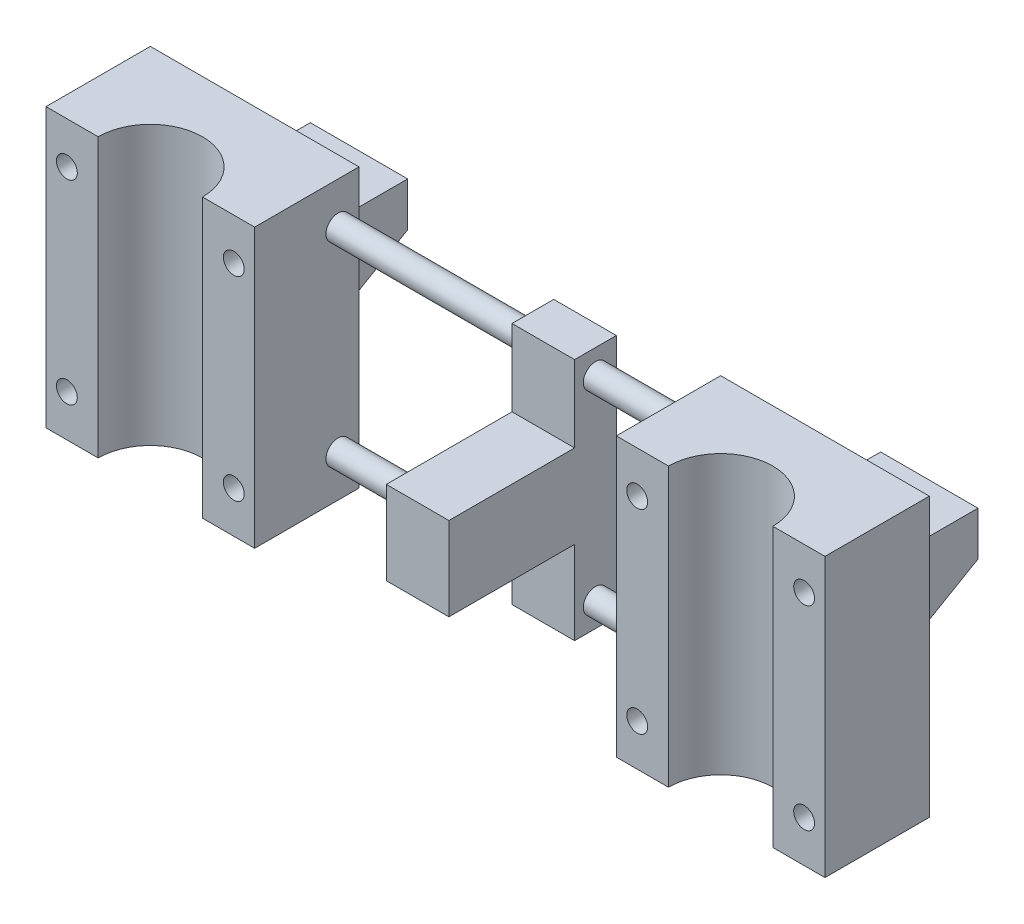
SolidWorks part; units mm, degrees
ref_plane "Front Plane" through (0, 0, 0) normal (0, 0, 1) x (1, 0, 0)
ref_plane "Top Plane" through (0, 0, 0) normal (0, 1, 0) x (1, 0, 0)
ref_plane "Right Plane" through (0, 0, 0) normal (1, 0, 0) x (0, 0, -1)
sketch "Sketch1" plane through (0, 0, 0) normal (0, 0, 1) x (1, 0, 0)
  line L1 (0, 0) -> (30, 0)
  line L2 (0, 0) -> (0, 40)
  line L3 (0, 40) -> (30, 40)
  line L4 (30, 0) -> (30, 40)
  dimension "D1" = 40
  dimension "D2" = 30
extrude "Boss-Extrude1" add sketch "Sketch1" along normal blind 15
sketch "Sketch2" plane through (0, 40, 0) normal (0, 1, 0) x (1, 0, 0)
  line L0 (30, -15) -> (0, -15) construction
  line L1 (7.5, -15) -> (22.5, -15)
  arc A0 (22.5, -15) -> (7.5, -15) centre (15, -15) ccw
  dimension "D1" = 15
extrude "Cut-Extrude1" cut sketch "Sketch2" against normal blind 49
sketch "Sketch3" plane through (0, 0, 15) normal (0, 0, 1) x (1, 0, 0)
  line L0 (7.5, 40) -> (0, 40) construction
  line L1 (0, 40) -> (0, 0) construction
  line L2 (30, 0) -> (30, 40) construction
  line L3 (30, 40) -> (22.5, 40) construction
  line L4 (22.5, 0) -> (30, 0) construction
  line L5 (0, 0) -> (7.5, 0) construction
  circle A0 centre (3, 34) radius 1.5
  circle A1 centre (3, 6) radius 1.5
  circle A2 centre (27, 34) radius 1.5
  circle A3 centre (27, 6) radius 1.5
  point P19 (26.25, 0)
  point P25 (3.75, 0)
  dimension "D1" = 3
  dimension "D2" = 3
  dimension "D3" = 3
  dimension "D4" = 3
  dimension "D5" = 6
  dimension "D6" = 3
  dimension "D7" = 3
  dimension "D8" = 6
  dimension "D9" = 6
  dimension "D10" = 3
  dimension "D11" = 3
  dimension "D12" = 6
extrude "Cut-Extrude2" cut sketch "Sketch3" against normal blind 49
sketch "Sketch4" plane through (30, 0, 0) normal (1, 0, 0) x (0, 0, -1)
  line L0 (-15, 40) -> (0, 40) construction
  line L1 (-15, 0) -> (0, 0) construction
  line L2 (0, 0) -> (0, 40) construction
  circle A0 centre (-3, 34) radius 1.75
  circle A1 centre (-3, 6) radius 1.75
  dimension "D1" = 3.5
  dimension "D2" = 3.5
  dimension "D3" = 6
  dimension "D4" = 6
  dimension "D5" = 3
  dimension "D6" = 3
extrude "Boss-Extrude2" add sketch "Sketch4" along normal blind 28
sketch "Sketch5" plane through (58, 0, 0) normal (1, 0, 0) x (0, 0, -1)
  line L0 (0, 0) -> (0, 40) construction
  line L1 (0, 37.5) -> (-6, 37.5)
  line L2 (0, 37.5) -> (0, 2.5)
  line L3 (0, 2.5) -> (-6, 2.5)
  line L4 (-6, 37.5) -> (-6, 2.5)
  circle A0 centre (-3, 34) radius 1.75 construction
  point P6 (-3, 37.5)
  dimension "D3" = 6
  dimension "D1" = 3.5
  dimension "D2" = 35
extrude "Boss-Extrude3" add sketch "Sketch5" along normal blind 9
sketch "Sketch6" plane through (67, 0, 0) normal (1, 0, 0) x (0, 0, -1)
  line L3 (-15, 40) -> (0, 40) construction
  line L4 (0, 2.5) -> (0, 37.5) construction
  line L6 (-15, 0) -> (0, 0) construction
  circle A0 centre (-3, 34) radius 1.75
  circle A1 centre (-3, 6) radius 1.75
  dimension "D1" = 3.5
  dimension "D2" = 3.5
  dimension "D3" = 6
  dimension "D4" = 6
  dimension "D5" = 3
extrude "Boss-Extrude4" add sketch "Sketch6" along normal blind 15
sketch "Sketch7" plane through (82, 0, 0) normal (1, 0, 0) x (0, 0, -1)
  line L1 (0, 40) -> (-15, 40)
  line L2 (0, 40) -> (0, 0)
  line L3 (0, 0) -> (-15, 0)
  line L4 (-15, 40) -> (-15, 0)
extrude "Boss-Extrude6" add sketch "Sketch7" along normal blind 30
sketch "Sketch9" plane through (0, 40, 0) normal (0, 1, 0) x (1, 0, 0)
  line L0 (112, -15) -> (82, -15) construction
  line L1 (89.5, -15) -> (104.5, -15)
  arc A0 (104.5, -15) -> (89.5, -15) centre (97, -15) ccw
  dimension "D1" = 15
extrude "Cut-Extrude3" cut sketch "Sketch9" against normal blind 59
sketch "Sketch10" plane through (0, 0, 15) normal (0, 0, 1) x (1, 0, 0)
  line L0 (89.5, 40) -> (82, 40) construction
  line L1 (82, 40) -> (82, 0) construction
  line L2 (112, 40) -> (112, 0) construction
  line L3 (112, 40) -> (104.5, 40) construction
  line L4 (112, 0) -> (104.5, 0) construction
  line L5 (89.5, 0) -> (82, 0) construction
  circle A0 centre (85, 34) radius 1.5
  circle A1 centre (109, 34) radius 1.5
  circle A2 centre (109, 6) radius 1.5
  circle A3 centre (85, 6) radius 1.5
  dimension "D1" = 3
  dimension "D2" = 6
  dimension "D3" = 3
  dimension "D4" = 3
  dimension "D5" = 6
  dimension "D6" = 3
  dimension "D7" = 6
  dimension "D8" = 6
  dimension "D9" = 3
extrude "Cut-Extrude4" cut sketch "Sketch10" against normal blind 59
sketch "Sketch14" plane through (0, 0, 0) normal (0, 0, -1) x (-1, 0, 0)
  line L0 (-97, 0) -> (-97, 40) construction
  line L1 (-104, 12) -> (-90, 12)
  line L2 (-104, 12) -> (-104, 27)
  line L3 (-104, 27) -> (-90, 27)
  line L4 (-90, 12) -> (-90, 27)
  line L5 (-104, 12) -> (-90, 27) construction
  line L6 (-104, 27) -> (-90, 12) construction
  line L7 (-112, 0) -> (-82, 0) construction
  point P0 (-97, 19.5)
  dimension "D1" = 15
  dimension "D2" = 14
  dimension "D3" = 12
extrude "Boss-Extrude8" add sketch "Sketch14" along normal blind 15
sketch "Sketch15" plane through (104, 0, 0) normal (1, 0, 0) x (0, 0, -1)
  line L0 (0, 12) -> (15, 20.6603)
  line L1 (15, 12) -> (0, 12) construction
  line L4 (15, 20.6603) -> (15, 12)
  line L5 (15, 12) -> (0, 12)
  dimension "D1" = 30
extrude "Cut-Extrude7" cut sketch "Sketch15" against normal blind 21
ref_plane "Plane1" through (56, 0, 0) normal (1, 0, 0) x (0, 0, -1)
mirror "Mirror1" about plane through (56, 0, 0) normal (1, 0, 0) of "Boss-Extrude8", "Cut-Extrude7"
sketch "Sketch17" plane through (0, 0, 6) normal (0, 0, 1) x (1, 0, 0)
  line L1 (58, 26.5) -> (67, 26.5)
  line L2 (58, 26.5) -> (58, 14.5)
  line L3 (58, 14.5) -> (67, 14.5)
  line L4 (67, 26.5) -> (67, 14.5)
  line L5 (67, 2.5) -> (58, 2.5) construction
  line L8 (58, 37.5) -> (58, 2.5) construction
  dimension "D1" = 12
  dimension "D2" = 9
  dimension "D3" = 12
extrude "Boss-Extrude10" add sketch "Sketch17" along normal blind 18.07
